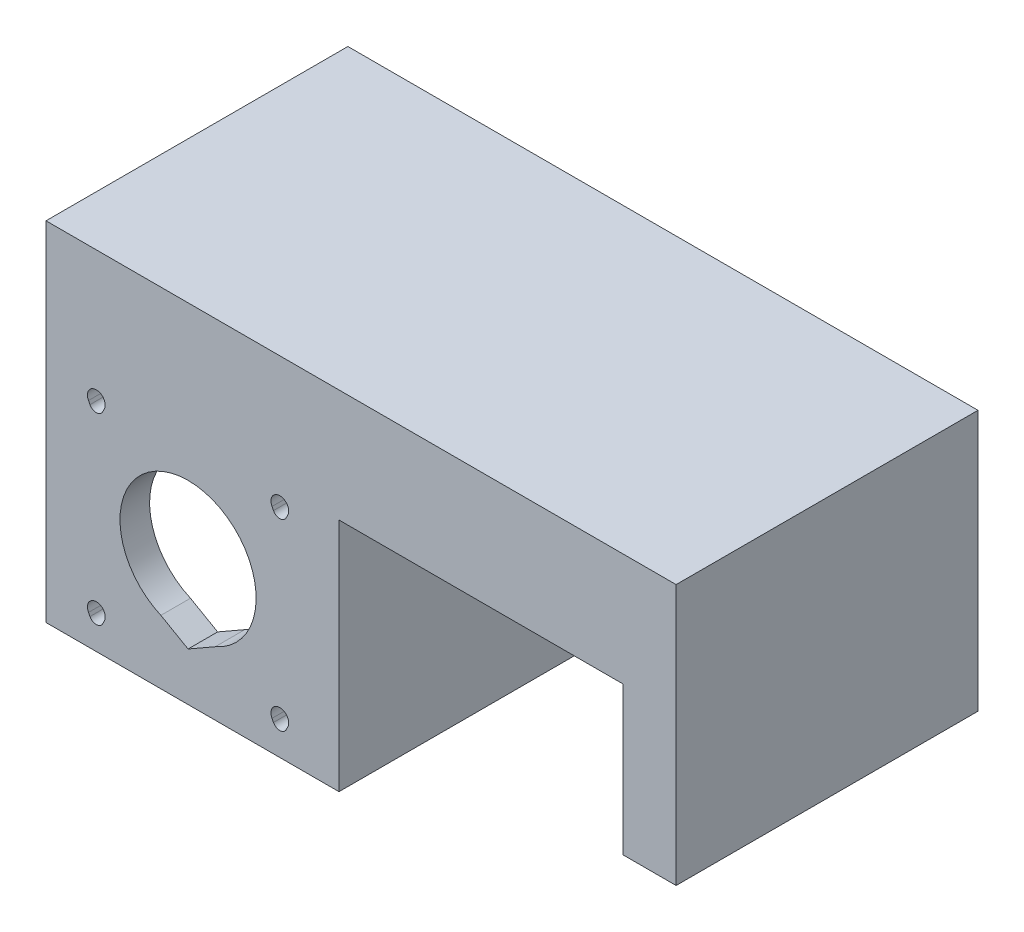
SolidWorks part; units mm, degrees
ref_plane "Front Plane" through (0, 0, 0) normal (0, 0, 1) x (1, 0, 0)
ref_plane "Top Plane" through (0, 0, 0) normal (0, 1, 0) x (1, 0, 0)
ref_plane "Right Plane" through (0, 0, 0) normal (1, 0, 0) x (0, 0, -1)
sketch "Sketch1" plane through (0, 0, 0) normal (0, 0, 1) x (1, 0, 0)
  line L1 (0, 0) -> (48, 0)
  line L2 (0, 0) -> (0, 53)
  line L3 (0, 53) -> (48, 53)
  line L4 (48, 0) -> (48, 53)
  dimension "D1" = 53
  dimension "D2" = 48
extrude "Boss-Extrude1" add sketch "Sketch1" along normal blind 10
sketch "Sketch2" plane through (0, 0, 0) normal (0, 0, -1) x (-1, 0, 0)
  line L0 (0, 53) -> (0, 0) construction
  line L1 (-48, 0) -> (0, 0)
  line L2 (-48, 0) -> (-48, -5.6163)
  line L3 (-48, -5.6163) -> (0, -5.6163)
  line L4 (0, 0) -> (0, -5.6163)
  dimension "D1" = 5.6163
extrude "Boss-Extrude2" add sketch "Sketch2" against normal blind 33.1918
sketch "Sketch4" plane through (0, 0, 10) normal (0, 0, 1) x (1, 0, 0)
  line L1 (0, 53) -> (4, 53)
  line L2 (0, 53) -> (0, 43)
  line L3 (0, 43) -> (4, 43)
  line L4 (4, 53) -> (4, 43)
  line L5 (48, 53) -> (44, 53)
  line L6 (48, 53) -> (48, 43)
  line L7 (48, 43) -> (44, 43)
  line L8 (44, 53) -> (44, 43)
  dimension "D1" = 10
  dimension "D2" = 4
extrude "Boss-Extrude4" add sketch "Sketch4" along normal blind 40
sketch "Sketch5" plane through (0, 0, 10) normal (0, 0, 1) x (1, 0, 0)
  line L0 (48, 0) -> (48, 43) construction
  line L1 (0, 0) -> (48, 0)
  line L2 (0, 0) -> (0, 10.8609)
  line L3 (0, 10.8609) -> (48, 10.8609)
  line L4 (48, 0) -> (48, 10.8609)
  dimension "D1" = 10.8609
extrude "Boss-Extrude5" add sketch "Sketch5" along normal up to surface (23.1918 mm away) up to face at (24, -2.8082, 33.1918)
sketch "Sketch6" plane through (0, -5.6163, 0) normal (0, -1, 0) x (1, 0, 0)
  line L0 (0, 0) -> (0, 28.1918) construction
  line L1 (0, 33.1918) -> (0, 0) construction
  line L2 (48, 33.1918) -> (48, 0) construction
  line L3 (0, 28.1918) -> (48, 28.1918)
  line L4 (0, 28.1918) -> (0, 33.1918)
  line L5 (0, 33.1918) -> (48, 33.1918)
  line L6 (48, 28.1918) -> (48, 33.1918)
  line L8 (48, 33.1918) -> (0, 33.1918) construction
  dimension "D2" = 5
extrude "Boss-Extrude6" add sketch "Sketch6" along normal blind 42.3
sketch "Sketch7" plane through (0, 0, 0) normal (-1, 0, 0) x (0, 0, 1)
  line L0 (33.1918, 10.8609) -> (10, 10.8609) construction
  line L1 (0, -5.6163) -> (-12.8082, -5.6163)
  line L2 (0, -5.6163) -> (0, 10.8609)
  line L3 (0, 10.8609) -> (-12.8082, 10.8609)
  line L4 (-12.8082, -5.6163) -> (-12.8082, 10.8609)
  line L5 (28.1918, -47.9163) -> (28.1918, -5.6163) construction
  dimension "D1" = 41
extrude "Boss-Extrude7" add sketch "Sketch7" against normal up to surface (48 mm away) up to face at (48, 10.6657, 24.2767)
sketch "Sketch8" plane through (0, 0, 28.1918) normal (0, 0, -1) x (-1, 0, 0)
  line L0 (-24, -26.6163) -> (-24, -5.6163) construction
  line L1 (0, -5.6163) -> (-48, -5.6163) construction
  line L3 (-8.5, -42.1163) -> (-39.5, -42.1163) construction
  line L4 (-8.5, -42.1163) -> (-8.5, -11.1163) construction
  line L5 (-8.5, -11.1163) -> (-39.5, -11.1163) construction
  line L6 (-39.5, -42.1163) -> (-39.5, -11.1163) construction
  line L7 (-8.5, -42.1163) -> (-39.5, -11.1163) construction
  line L8 (-8.5, -11.1163) -> (-39.5, -42.1163) construction
  circle A0 centre (-24, -26.6163) radius 11.5
  circle A1 centre (-39.5, -11.1163) radius 1.5
  circle A2 centre (-39.5, -42.1163) radius 1.5
  circle A3 centre (-8.5, -11.1163) radius 1.5
  circle A4 centre (-8.5, -42.1163) radius 1.5
  dimension "D2" = 23
  dimension "D4" = 3
  dimension "D1" = 21
  dimension "D3" = 31
extrude "Cut-Extrude1" cut sketch "Sketch8" against normal up to next
fillet "Fillet1" radius 10 1 edges at (24, 10.8609, 0)
fillet "Fillet2" radius 4 2 edges at (2, 43, 10) (46, 43, 10)
sketch "Sketch9" plane through (48, 0, 0) normal (1, 0, 0) x (0, 0, -1)
  line L1 (12.8082, 10.8609) -> (17.8082, 10.8609)
  line L2 (12.8082, 10.8609) -> (12.8082, -5.6163)
  line L3 (12.8082, -5.6163) -> (17.8082, -5.6163)
  line L4 (17.8082, 10.8609) -> (17.8082, -5.6163)
  line L5 (-28.1918, -5.6163) -> (12.8082, -5.6163) construction
  dimension "D1" = 5
extrude "Boss-Extrude9" add sketch "Sketch9" against normal up to surface (48 mm away) contours L4 L3 L2 L1 up to face at (0, 13.3569, 15.8852)
sketch "Sketch10" plane through (48, 0, 0) normal (1, 0, 0) x (0, 0, -1)
  line L0 (17.8082, 10.8609) -> (-33.1918, 10.8609)
  line L1 (-33.1918, 10.8609) -> (-76.8871, 43.9021)
  line L2 (-76.8871, 43.9021) -> (-50.7941, 74.4365)
  line L3 (-50.7941, 74.4365) -> (27.2075, 71.1055)
  line L4 (27.2075, 71.1055) -> (17.8082, 10.8609)
extrude "Cut-Extrude2" cut sketch "Sketch10" against normal through all
sketch "Sketch11" plane through (48, 0, 0) normal (1, 0, 0) x (0, 0, -1)
  line L1 (-33.1918, 10.8609) -> (17.8082, 10.8609)
  line L2 (-33.1918, 10.8609) -> (-33.1918, -5.6163)
  line L3 (-33.1918, -5.6163) -> (17.8082, -5.6163)
  line L4 (17.8082, 10.8609) -> (17.8082, -5.6163)
extrude "Boss-Extrude10" add sketch "Sketch11" along normal blind 49.45
sketch "Sketch12" plane through (0, 0, 28.1918) normal (0, 0, -1) x (-1, 0, 0)
  line L0 (0, -47.9163) -> (-48, -47.9163) construction
  line L2 (-48, -5.6163) -> (-48, -47.9163) construction
  line L3 (-48, -47.9163) -> (-45, -47.9163)
  line L4 (-45, -5.6163) -> (-45, -47.9163)
  line L5 (-49.5, -5.6163) -> (-45, -5.6163)
  line L7 (-48, -5.6163) -> (-48, -47.9163) construction
  line L8 (-48, -47.9163) -> (-49.5, -47.9163)
  line L9 (-49.5, -5.6163) -> (-49.5, -47.9163)
  dimension "D1" = 3
  dimension "D2" = 1.5
extrude "Boss-Extrude11" add sketch "Sketch12" along normal up to surface (46 mm away) up to face at (48.725, 2.6223, -17.8082)
sketch "Sketch16" plane through (0, -5.6163, 0) normal (0, -1, 0) x (1, 0, 0)
  line L1 (49.5, -17.8082) -> (97.45, -17.8082)
  line L2 (49.5, -17.8082) -> (49.5, 33.1918)
  line L3 (49.5, 33.1918) -> (97.45, 33.1918)
  line L4 (97.45, -17.8082) -> (97.45, 33.1918)
extrude "Boss-Extrude14" add sketch "Sketch16" along normal blind 2.55
sketch "Sketch14" plane through (49.5, 0, 0) normal (1, 0, 0) x (0, 0, -1)
  line L1 (-28.1918, -5.6163) -> (-33.1918, -5.6163)
  line L2 (-28.1918, -5.6163) -> (-28.1918, -47.9163)
  line L3 (-28.1918, -47.9163) -> (-33.1918, -47.9163)
  line L4 (-33.1918, -5.6163) -> (-33.1918, -47.9163)
extrude "Boss-Extrude13" add sketch "Sketch14" against normal up to surface (1.5 mm away) up to face at (48, -26.7663, 30.6918)
sketch "Sketch17" plane through (97.45, 0, 0) normal (1, 0, 0) x (0, 0, -1)
  line L1 (-33.1918, -8.1663) -> (17.8082, -8.1663)
  line L2 (-33.1918, -8.1663) -> (-33.1918, 10.8609)
  line L3 (-33.1918, 10.8609) -> (17.8082, 10.8609)
  line L4 (17.8082, -8.1663) -> (17.8082, 10.8609)
extrude "Boss-Extrude15" add sketch "Sketch17" along normal blind 9
sketch "Sketch18" plane through (0, -8.1663, 0) normal (0, -1, 0) x (1, 0, 0)
  line L0 (106.45, 33.1918) -> (106.45, -17.8082) construction
  line L1 (49.5, -17.8082) -> (106.45, -17.8082)
  line L2 (49.5, -17.8082) -> (49.5, -9.8082)
  line L3 (49.5, -9.8082) -> (97.45, -9.8082)
  line L4 (106.45, -17.8082) -> (106.45, -9.8082)
  line L5 (106.45, 33.1918) -> (49.5, 33.1918) construction
  line L7 (106.45, -9.8082) -> (106.45, 33.1918)
  line L8 (106.45, 33.1918) -> (97.45, 33.1918)
  line L9 (97.45, -9.8082) -> (97.45, 33.1918)
  dimension "D1" = 9
  dimension "D2" = 8
extrude "Boss-Extrude16" add sketch "Sketch18" along normal blind 25
sketch "Sketch19" plane through (0, 0, -9.8082) normal (0, 0, 1) x (1, 0, 0)
  line L0 (49.5, -8.1663) -> (58.475, -26.1663) construction
  line L1 (58.475, -26.1663) -> (88.475, -26.1663) construction
  line L2 (88.475, -26.1663) -> (97.45, -8.1663) construction
  line L3 (97.45, -8.1663) -> (49.5, -8.1663) construction
  circle A0 centre (58.475, -26.1663) radius 1.9304
  circle A1 centre (88.475, -26.1663) radius 1.9304
  dimension "D3" = 3.8608
  dimension "D1" = 30
  dimension "D2" = 18
extrude "Cut-Extrude3" cut sketch "Sketch19" against normal through all
sketch "Sketch20" plane through (0, 0, 33.1918) normal (0, 0, 1) x (1, 0, 0)
  line L0 (8.5, -11.1163) -> (8.5, -42.1163) construction
  line L1 (7.1848, -11.8376) -> (7.4338, -12.3197)
  line L2 (9.8152, -11.8376) -> (9.5662, -12.3197)
  line L3 (7.1848, -42.8376) -> (7.4338, -43.3197)
  line L4 (9.8152, -42.8376) -> (9.5662, -43.3197)
  line L5 (24, -26.6163) -> (24, -1.3647) construction
  line L6 (38.1848, -42.8376) -> (38.4338, -43.3197)
  line L7 (40.8152, -42.8376) -> (40.5662, -43.3197)
  line L8 (38.1848, -11.8376) -> (38.4338, -12.3197)
  line L9 (40.8152, -11.8376) -> (40.5662, -12.3197)
  line L10 (19.4053, -37.1586) -> (24, -39.7872)
  line L11 (28.5947, -37.1586) -> (24, -39.7872)
  circle A0 centre (8.5, -11.1163) radius 1.5 construction
  arc A1 (7.1848, -11.8376) -> (9.8152, -11.8376) centre (8.5, -11.1163) ccw
  arc A2 (7.1848, -42.8376) -> (9.8152, -42.8376) centre (8.5, -42.1163) ccw
  arc A3 (40.8152, -42.8376) -> (38.1848, -42.8376) centre (39.5, -42.1163) cw
  arc A4 (40.8152, -11.8376) -> (38.1848, -11.8376) centre (39.5, -11.1163) cw
  arc A5 (38.4338, -12.3197) -> (40.5662, -12.3197) centre (39.5, -11.7691) ccw
  arc A6 (19.4053, -37.1586) -> (28.5947, -37.1586) centre (24, -26.6163) ccw
  arc A7 (38.4338, -43.3197) -> (40.5662, -43.3197) centre (39.5, -42.7691) ccw
  arc A8 (7.4338, -43.3197) -> (9.5662, -43.3197) centre (8.5, -42.7691) ccw
  arc A9 (7.4338, -12.3197) -> (9.5662, -12.3197) centre (8.5, -11.7691) ccw
  point P26 (39.5, -14.3844)
  point P33 (39.5, -45.3844)
  point P36 (8.5, -45.3844)
  point P39 (8.5, -14.3844)
  dimension "D2" = 1.2
  dimension "D1" = 2
extrude "Cut-Extrude4" cut sketch "Sketch20" against normal up to next
